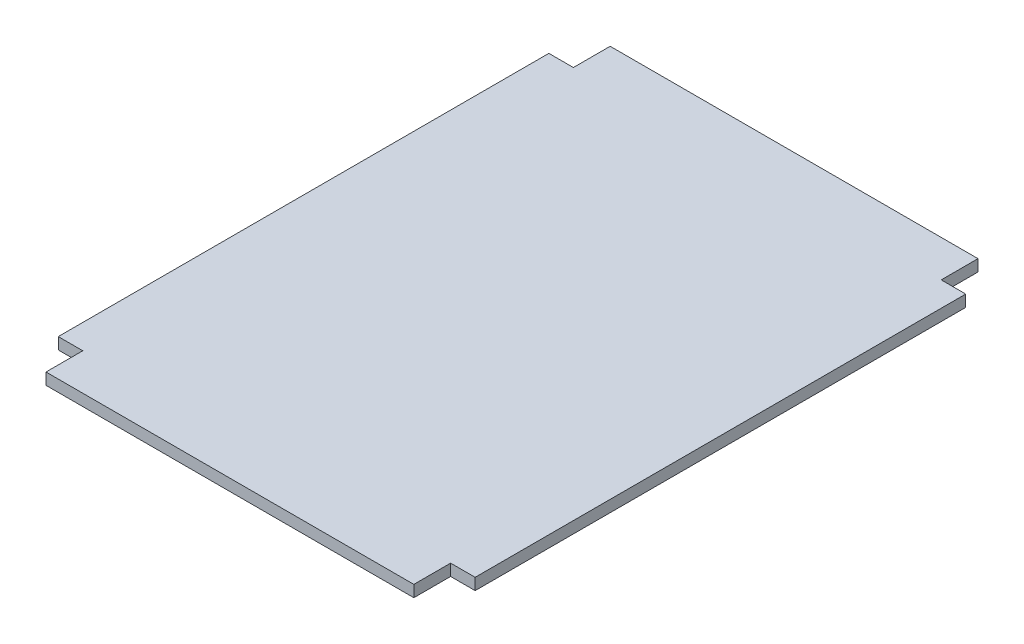
SolidWorks part; units mm, degrees
ref_plane "Front Plane" through (0, 0, 0) normal (0, 0, 1) x (1, 0, 0)
ref_plane "Top Plane" through (0, 0, 0) normal (0, 1, 0) x (1, 0, 0)
ref_plane "Right Plane" through (0, 0, 0) normal (1, 0, 0) x (0, 0, -1)
sketch "Sketch1" plane through (0, 0, 0) normal (0, 1, 0) x (1, 0, 0)
  line L0 (-53.9623, 66.4972) -> (53.9623, 66.4972) construction
  line L1 (53.9623, -73.025) -> (-53.9623, -73.025)
  line L2 (53.9623, -73.025) -> (53.9623, 73.025)
  line L3 (53.9623, 73.025) -> (-53.9623, 73.025)
  line L4 (-53.9623, -73.025) -> (-53.9623, 73.025)
  line L5 (53.9623, -73.025) -> (-53.9623, 73.025) construction
  line L6 (53.9623, 73.025) -> (-53.9623, -73.025) construction
  line L7 (-53.9623, -66.4972) -> (53.9623, -66.4972) construction
  line L8 (-53.9623, 66.4972) -> (-53.9623, -66.4972) construction
  line L9 (53.9623, 66.4972) -> (53.9623, -66.4972) construction
  line L20 (-53.9623, -73.025) -> (-47.6123, -73.025)
  line L29 (-53.9623, -73.025) -> (-53.9623, -63.5)
  line L34 (-53.9623, -63.5) -> (-47.6123, -63.5)
  line L39 (-47.6123, -73.025) -> (-47.6123, -63.5)
  line L40 (53.9623, -73.025) -> (47.6123, -73.025)
  line L41 (53.9623, -73.025) -> (53.9623, -63.5)
  line L42 (53.9623, -63.5) -> (47.6123, -63.5)
  line L43 (47.6123, -73.025) -> (47.6123, -63.5)
  line L44 (53.9623, 73.025) -> (47.6123, 73.025)
  line L45 (53.9623, 73.025) -> (53.9623, 63.5)
  line L46 (53.9623, 63.5) -> (47.6123, 63.5)
  line L47 (47.6123, 73.025) -> (47.6123, 63.5)
  line L48 (-53.9623, 73.025) -> (-47.6123, 73.025)
  line L49 (-53.9623, 73.025) -> (-53.9623, 63.5)
  line L50 (-53.9623, 63.5) -> (-47.6123, 63.5)
  line L51 (-47.6123, 73.025) -> (-47.6123, 63.5)
  point P0 (0, 0)
  point P10 (53.9623, 0)
  point P11 (53.9623, 0)
  dimension "D1" = 107.9246
  dimension "D2" = 146.05
  dimension "D3" = 132.9944
  dimension "D4" = 6.35
  dimension "D5" = 127
extrude "Boss-Extrude1" add sketch "Sketch1" along normal blind 2.9972
